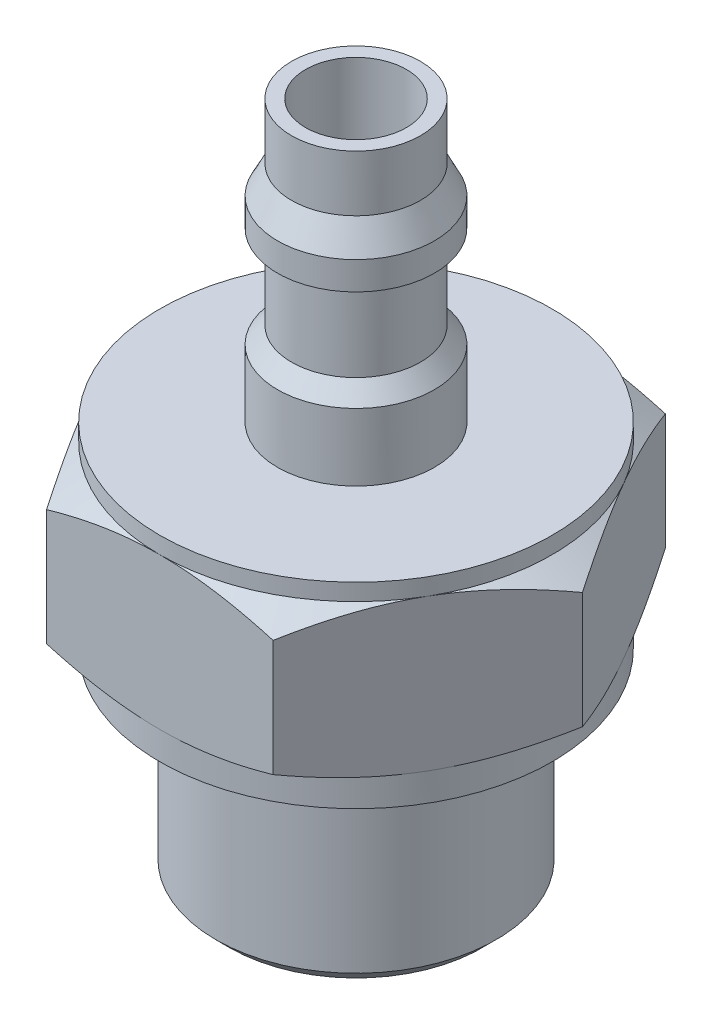
SolidWorks part; units mm, degrees
ref_plane "Front" through (0, 0, 0) normal (0, 0, 1) x (1, 0, 0)
ref_plane "Top" through (0, 0, 0) normal (0, 1, 0) x (1, 0, 0)
ref_plane "Right" through (0, 0, 0) normal (1, 0, 0) x (0, 0, -1)
ref_plane "Thread Length" through (0, 4, 0) normal (0, 1, 0) x (-1, 0, 0)
ref_plane "Total Height" through (0, 12, 0) normal (0, 1, 0) x (-1, 0, 0)
ref_plane "Nut Thickness" through (0, 6.7, 0) normal (0, 1, 0) x (-1, 0, 0)
sketch "Threads_Sketch" plane through (0, 0, 0) normal (0, 0, 1) x (1, 0, 0)
  line L0 (0, 0) -> (0, 31.3779) construction
  line L1 (0, 0) -> (0, 4)
  line L2 (0, 4) -> (-2.5, 4)
  line L3 (-2.5, 4) -> (-2.5, 0)
  line L4 (-2.5, 0) -> (0, 0)
  line L5 (50, 4) -> (-50, 4) construction
  point P6 (-2.5, 5)
  dimension "a" = 5
  dimension "d" = 5
  dimension "Angle" = 90
revolve "Threads" add sketch "Threads_Sketch" angle 360 about L0
chamfer "Threads Cham" distance 0.25 1 edges at (0, 0, -2.5)
sketch "Nut_Sketch" plane through (0, 4, 0) normal (0, 1, 0) x (-1, 0, 0)
  line L1 (-4.0415, 0) -> (-2.0207, -3.5)
  line L2 (-2.0207, -3.5) -> (2.0207, -3.5)
  line L3 (2.0207, -3.5) -> (4.0415, 0)
  line L4 (4.0415, 0) -> (2.0207, 3.5)
  line L5 (2.0207, 3.5) -> (-2.0207, 3.5)
  line L6 (-2.0207, 3.5) -> (-4.0415, 0)
  circle A0 centre (0, 0) radius 3.5 construction
  point P1 (3.5, 0)
  dimension "Flats" = 7
extrude "Nut" add sketch "Nut_Sketch" along normal up to surface (2.7 mm away) up to plane "Nut Thickness"
sketch "Nut Cham_Sketch" plane through (0, 0, 0) normal (0, 0, 1) x (1, 0, 0)
  line L0 (-4.0415, 5.35) -> (0.2879, 5.35) construction
  line L1 (-4.0415, 6.7) -> (-4.0415, 4) construction
  line L2 (-4.0415, 4.3126) -> (-4.0415, 4)
  line L3 (-4.0415, 4) -> (-3.5, 4)
  line L4 (-3.5, 4) -> (-4.0415, 4.3126)
  line L5 (-3.5, 6.7) -> (-4.0415, 6.3874)
  line L6 (-4.0415, 6.7) -> (-3.5, 6.7)
  line L7 (-4.0415, 6.3874) -> (-4.0415, 6.7)
  line L8 (0, 0) -> (0, 9.8857) construction
  line L9 (0, 0) -> (0, 31.3779) construction
  dimension "Angle" = 30
revolve "Nut Cham" cut sketch "Nut Cham_Sketch" angle 360 about L8
sketch "Gasket_Sketch" plane through (0, 4, 0) normal (0, -1, 0) x (1, 0, 0)
  circle A0 centre (0, 0) radius 3.5
  dimension "Dia" = 7
extrude "Gasket" add sketch "Gasket_Sketch" along normal blind 0.5
sketch "Stem_Sketch" plane through (0, 6.7, 0) normal (0, 1, 0) x (-1, 0, 0)
  circle A0 centre (0, 0) radius 1.15
  point P3 (1.15, 0)
  dimension "Dia" = 2.3
extrude "Stem" add sketch "Stem_Sketch" along normal up to surface (5.3 mm away) up to plane "Total Height"
sketch "Top Flat_Sketch" plane through (0, 6.7, 0) normal (0, 1, 0) x (-1, 0, 0)
  circle A0 centre (0, 0) radius 3.5
  dimension "Dia" = 7
extrude "Top Flat" add sketch "Top Flat_Sketch" along normal blind 0.3
sketch "Outside Barb_Sketch" plane through (0, 0, 0) normal (0, 0, 1) x (1, 0, 0)
  line L0 (0, 0) -> (0, 10.166) construction
  line L1 (0, 12) -> (0, 7) construction
  line L2 (0, 11) -> (-1.15, 11)
  line L3 (-1.15, 11) -> (-1.4, 10.5)
  line L4 (-1.4, 10.5) -> (-1.4, 10)
  line L5 (-1.4, 10) -> (0, 10)
  line L6 (0, 10) -> (0, 11)
  line L8 (1.15, 12) -> (-1.15, 12) construction
  dimension "Loc" = 1
  dimension "Thickness" = 1
  dimension "Flat" = 0.5
  dimension "OD" = 2.8
revolve "Outside Barb" add sketch "Outside Barb_Sketch" angle 360 about L0
sketch "Inside Barb 1_Sketch" [suppressed] plane through (0, 0, 0) normal (0, 0, 1) x (1, 0, 0)
  line L0 (0, 0) -> (0, 10.3128) construction
  line L1 (0, 7.9) -> (0, 5) construction
  line L2 (0, 7.2) -> (-1, 7.2)
  line L3 (-1, 7.2) -> (-1.3, 6.5)
  line L4 (-1.3, 6.5) -> (-1.3, 6.4)
  line L5 (-1.3, 6.4) -> (0, 6.4)
  line L6 (0, 6.4) -> (0, 7.2)
  line L7 (-1.3, 8) -> (-1.3, 7.9) construction
  line L8 (0, 7.9) -> (0, 8.7) construction
  line L9 (1, 9.5) -> (-1, 9.5) construction
  dimension "Loc" = 2.3
revolve "Inside Barb 1" [suppressed] add sketch "Inside Barb 1_Sketch" angle 360 about L0
sketch "Inside Barb 2_Sketch" plane through (0, 0, 0) normal (0, 0, 1) x (1, 0, 0)
  line L0 (0, 0) -> (0, 10.7713) construction
  line L1 (0, 10) -> (0, 7) construction
  line L2 (0, 8.5) -> (-1.15, 8.5)
  line L3 (-1.15, 8.5) -> (-1.4, 8.2)
  line L4 (-1.4, 8.2) -> (-1.4, 6.7)
  line L5 (-1.4, 6.7) -> (0, 6.7)
  line L6 (0, 6.7) -> (0, 8.5)
  line L7 (50, 6.7) -> (-50, 6.7) construction
  line L9 (1.15, 12) -> (-1.15, 12) construction
  line L11 (-1.4, 10.5) -> (-1.4, 10) construction
  dimension "Loc" = 3.5
  dimension "Flat" = 1.5
revolve "Inside Barb 2" add sketch "Inside Barb 2_Sketch" angle 360 about L0
sketch "Port_Sketch" plane through (0, 0, 0) normal (0, 1, 0) x (1, 0, 0)
  circle A0 centre (0, 0) radius 0.9
  dimension "Dia" = 1.8
extrude "Port" cut sketch "Port_Sketch" along normal through all
